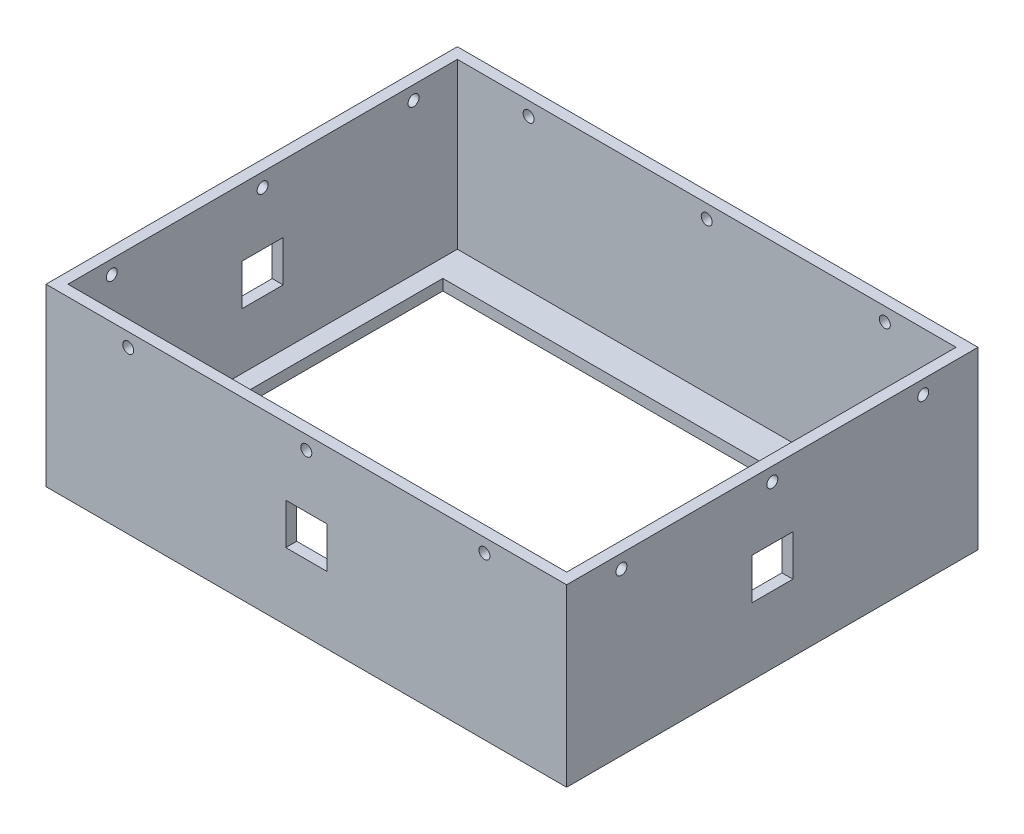
SolidWorks part; units mm, degrees
ref_plane "Front Plane" through (0, 0, 0) normal (0, 0, 1) x (1, 0, 0)
ref_plane "Top Plane" through (0, 0, 0) normal (0, 1, 0) x (1, 0, 0)
ref_plane "Right Plane" through (0, 0, 0) normal (1, 0, 0) x (0, 0, -1)
sketch "Sketch1" plane through (0, 0, 0) normal (0, 1, 0) x (1, 0, 0)
  line L9 (97.9981, 60.5564) -> (97.9981, -81.5564)
  line L13 (-83.9981, -81.5564) -> (97.9981, -81.5564)
  line L14 (-87.9981, 64.5564) -> (-87.9981, -85.5564)
  line L17 (-87.9981, -85.5564) -> (101.9981, -85.5564)
  line L18 (101.9981, 64.5564) -> (101.9981, -85.5564)
  line L19 (101.9981, 64.5564) -> (-87.9981, 64.5564)
  line L21 (-83.9981, 60.5564) -> (-83.9981, -81.5564)
  line L25 (16.3152, 60.5564) -> (97.9981, 60.5564)
  line L26 (16.3152, 60.5564) -> (-83.9981, 60.5564)
  point P0 (0, 0)
  point P1 (2, -5.5)
  dimension "D1" = 4
  dimension "D2" = 4
  dimension "D3" = 4
  dimension "D4" = 4
extrude "Boss-Extrude1" add sketch "Sketch1" along normal blind 60
sketch "Sketch2" plane through (0, 0, 0) normal (0, -1, 0) x (1, 0, 0)
  line L1 (101.9981, -64.5564) -> (-87.9981, -64.5564)
  line L2 (101.9981, -64.5564) -> (101.9981, 85.5564)
  line L3 (101.9981, 85.5564) -> (-87.9981, 85.5564)
  line L4 (-87.9981, -64.5564) -> (-87.9981, 85.5564)
extrude "Boss-Extrude2" add sketch "Sketch2" along normal blind 4
sketch "Sketch3" plane through (0, 0, 0) normal (0, 1, 0) x (1, 0, 0)
  line L7 (-83.9981, -81.5564) -> (97.9981, -81.5564) construction
  line L8 (91.9981, -76.5564) -> (-77.4219, -76.5564)
  line L9 (91.9981, -76.5564) -> (91.9981, 48.6936)
  line L10 (91.9981, 48.6936) -> (-77.4219, 48.6936)
  line L11 (-77.4219, -76.5564) -> (-77.4219, 48.6936)
  line L12 (97.9981, -81.5564) -> (97.9981, 60.5564) construction
  dimension "D1" = 5
  dimension "D2" = 6
  dimension "D3" = 125.25
  dimension "D4" = 169.42
extrude "Cut-Extrude1" cut sketch "Sketch3" against normal blind 4
sketch "Sketch4" plane through (-87.9981, 0, 0) normal (-1, 0, 0) x (0, 0, 1)
  line L0 (-64.5564, 60) -> (85.5564, 60) construction
  line L1 (2.9986, 35.5) -> (17.9986, 35.5)
  line L2 (2.9986, 35.5) -> (2.9986, 20.5)
  line L3 (2.9986, 20.5) -> (17.9986, 20.5)
  line L4 (17.9986, 35.5) -> (17.9986, 20.5)
  line L5 (2.9986, 35.5) -> (17.9986, 20.5) construction
  line L6 (2.9986, 20.5) -> (17.9986, 35.5) construction
  line L7 (-64.5564, 60) -> (-64.5564, -4) construction
  point P0 (10.4986, 28)
  dimension "D1" = 15
  dimension "D2" = 15
  dimension "D3" = 32
  dimension "D4" = 75.055
extrude "Cut-Extrude2" cut sketch "Sketch4" against normal blind 222
sketch "Sketch6" plane through (0, 0, 85.5564) normal (0, 0, 1) x (1, 0, 0)
  line L0 (-87.9981, 60) -> (101.9981, 60) construction
  line L1 (-0.4981, 35.5) -> (14.5019, 35.5)
  line L2 (-0.4981, 35.5) -> (-0.4981, 20.5)
  line L3 (-0.4981, 20.5) -> (14.5019, 20.5)
  line L4 (14.5019, 35.5) -> (14.5019, 20.5)
  line L5 (-0.4981, 35.5) -> (14.5019, 20.5) construction
  line L6 (-0.4981, 20.5) -> (14.5019, 35.5) construction
  line L7 (-87.9981, 60) -> (-87.9981, -4) construction
  point P0 (7.0019, 28)
  dimension "D1" = 15
  dimension "D2" = 15
  dimension "D3" = 32
  dimension "D4" = 95
extrude "Cut-Extrude3" cut sketch "Sketch6" against normal blind 50
sketch "Sketch7" plane through (101.9981, 0, 0) normal (1, 0, 0) x (0, 0, -1)
  line L0 (-85.5564, 60) -> (-85.5564, -4) construction
  line L1 (64.5564, 60) -> (64.5564, -4) construction
  line L2 (-85.5564, 60) -> (64.5564, 60) construction
  circle A0 centre (-65.5564, 55) radius 2
  circle A1 centre (-10.5014, 55) radius 2
  circle A2 centre (44.5564, 55) radius 2
  point P6 (0, 0)
  point P9 (0, 0)
  point P12 (0, 0)
  dimension "D4" = 5
  dimension "D1" = 20
  dimension "D2" = 75.055
  dimension "D3" = 20
  dimension "D5" = 5
  dimension "D6" = 5
extrude "Cut-Extrude4" cut sketch "Sketch7" against normal blind 220
sketch "Sketch8" plane through (0, 0, -64.5564) normal (0, 0, -1) x (-1, 0, 0)
  line L0 (-101.9981, 60) -> (87.9981, 60) construction
  line L1 (-101.9981, 60) -> (-101.9981, -4) construction
  line L2 (87.9981, 60) -> (87.9981, -4) construction
  circle A0 centre (-71.9981, 55) radius 2
  circle A1 centre (-6.9981, 55) radius 2
  circle A2 centre (57.9981, 55) radius 2
  point P8 (0, 0)
  dimension "D1" = 5
  dimension "D2" = 5
  dimension "D3" = 5
  dimension "D4" = 95
  dimension "D5" = 30
  dimension "D6" = 30
extrude "Cut-Extrude5" cut sketch "Sketch8" against normal blind 220
